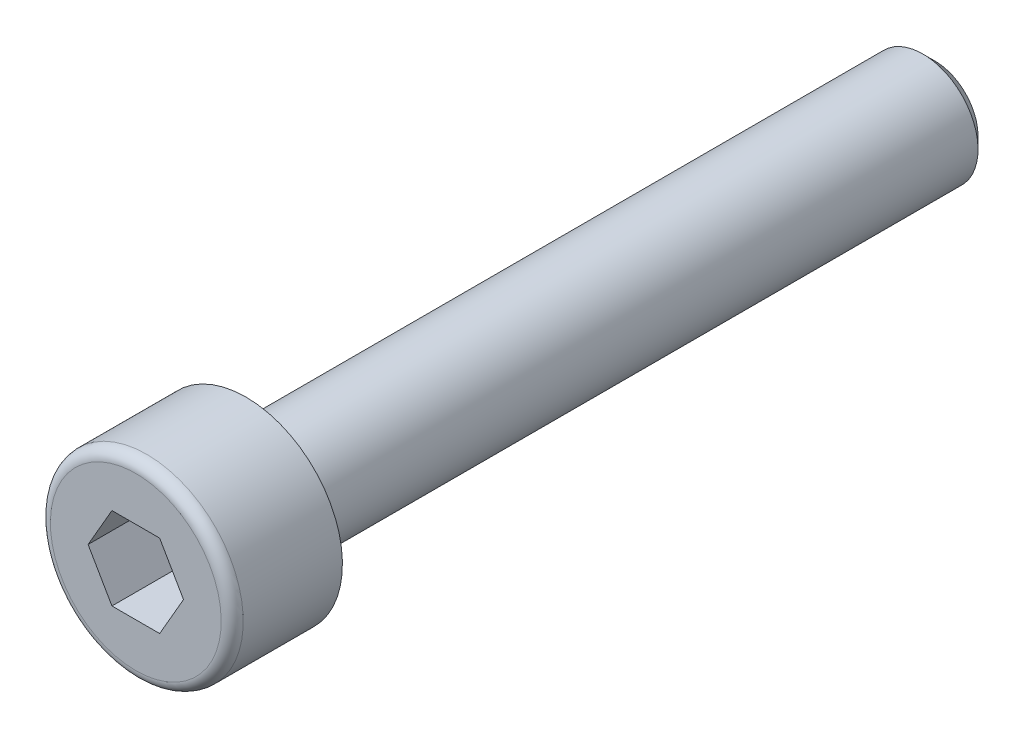
SolidWorks part; units mm, degrees
ref_plane "Plan de face" through (0, 0, 0) normal (0, 0, 1) x (1, 0, 0)
ref_plane "Plan de dessus" through (0, 0, 0) normal (0, 1, 0) x (1, 0, 0)
ref_plane "Plan de droite" through (0, 0, 0) normal (1, 0, 0) x (0, 0, -1)
ref_plane "Plan1" through (0, 0, 0) normal (0, -1, 0) x (1, 0, 0)
sketch "Esquisse1" plane through (0, 0, 0) normal (0, -1, 0) x (1, 0, 0)
  line L0 (3.5, 4) -> (0, 4)
  line L1 (0, 4) -> (0, -0.2)
  line L2 (0, -0.2) -> (2, -0.2)
  line L3 (2.2, 0) -> (3.5, 0)
  line L4 (3.5, 0) -> (3.5, 4)
  line L5 (0, 4) -> (0, -0.2) construction
  arc A0 (2, -0.2) -> (2.2, 0) centre (2.2, -0.2) cw
  circle A1 centre (2, 0) radius 0.04
revolve "Révolution1" add sketch "Esquisse1" angle 360 about L5
sketch "Esquisse2" plane through (0, 0, 4) normal (0, 0, 1) x (1, 0, 0)
  line L0 (1.7321, 0) -> (0.866, 1.5)
  line L1 (0.866, 1.5) -> (-0.866, 1.5)
  line L2 (-0.866, 1.5) -> (-1.7321, 0)
  line L3 (-1.7321, 0) -> (-0.866, -1.5)
  line L4 (-0.866, -1.5) -> (0.866, -1.5)
  line L5 (0.866, -1.5) -> (1.7321, 0)
extrude "Enlèv. mat.-Extru.1" cut sketch "Esquisse2" against normal blind 2.993
sketch "Esquisse3" plane through (0, 0, -0.2) normal (0, 0, -1) x (-1, 0, 0)
  circle A0 centre (0, 0) radius 2
  dimension "D1" = 4
extrude "Boss.-Extru.1" add sketch "Esquisse3" along normal blind 24.8
chamfer "Chanfrein1" distance 0.4294 angle 45 1 edges at (0, 2, -25)
fillet "Congé1" radius 0.4 1 edges at (0, 3.5, 4)
